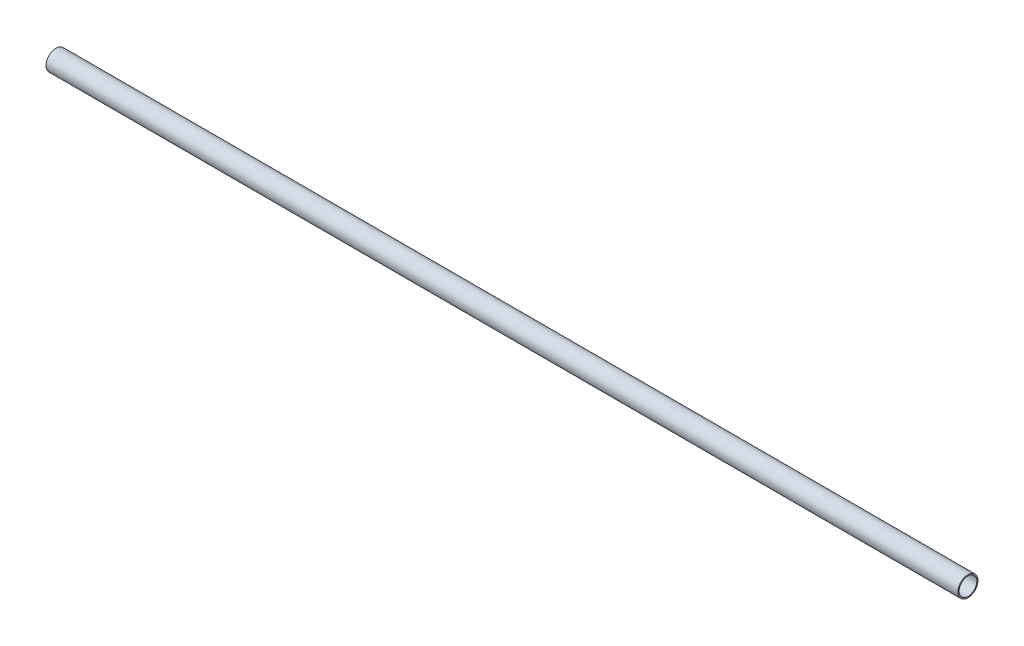
SolidWorks part; units mm, degrees
material "Galvanized Steel"
ref_plane "Front Plane" through (0, 0, 0) normal (0, 0, 1) x (1, 0, 0)
ref_plane "Top Plane" through (0, 0, 0) normal (0, 1, 0) x (1, 0, 0)
ref_plane "Right Plane" through (0, 0, 0) normal (1, 0, 0) x (0, 0, -1)
sketch "Sketch1" plane through (0, 0, 0) normal (1, 0, 0) x (0, 0, -1)
  circle A0 centre (0, 0) radius 7.8994
  circle A1 centre (0, 0) radius 8.9662
  dimension "D1" = 15.7988
  dimension "D2" = 17.9324
extrude "Boss-Extrude1" add sketch "Sketch1" along normal blind 812.8
